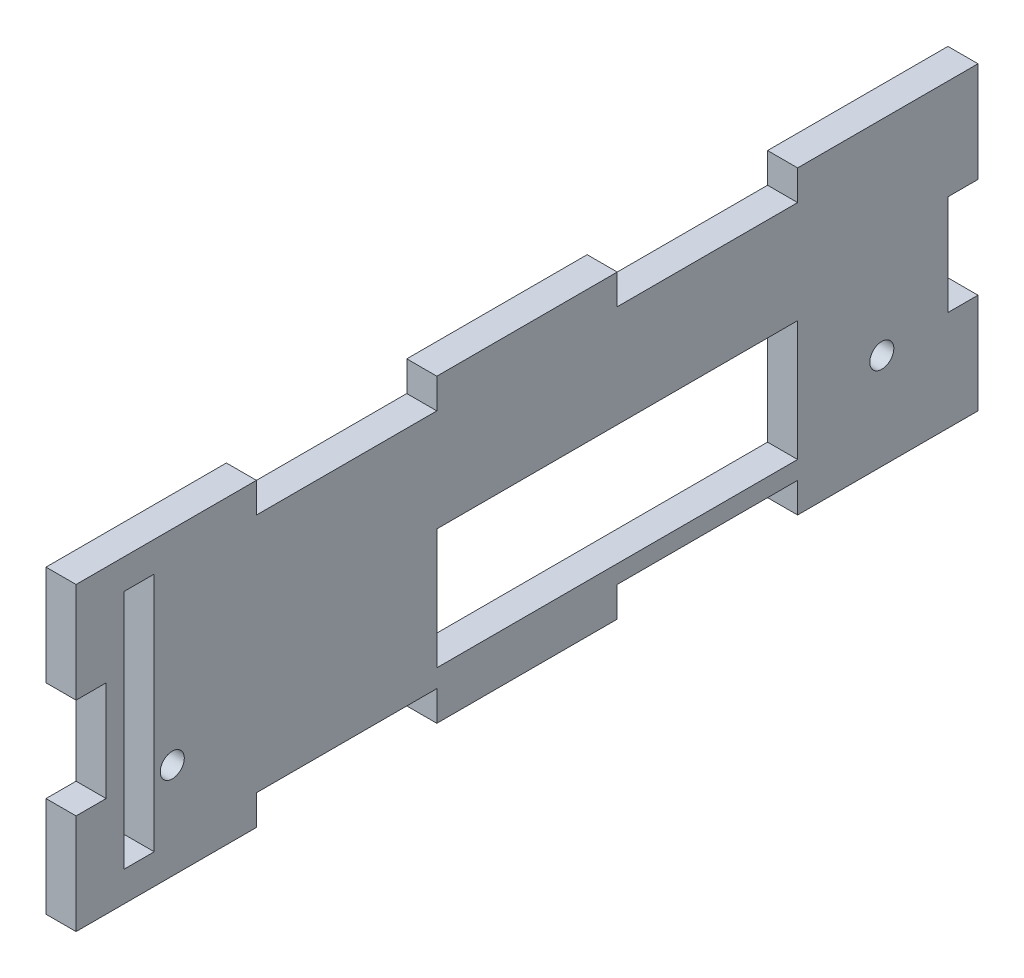
SolidWorks part; units mm, degrees
ref_plane "Alzado" through (0, 0, 0) normal (0, 0, 1) x (1, 0, 0)
ref_plane "Planta" through (0, 0, 0) normal (0, 1, 0) x (1, 0, 0)
ref_plane "Vista lateral" through (0, 0, 0) normal (1, 0, 0) x (0, 0, -1)
sketch "Croquis1" plane through (0, 0, 0) normal (1, 0, 0) x (0, 0, -1)
  line L0 (0, 33.3333) -> (5, 33.3333)
  line L1 (0, 0) -> (30, 0)
  line L2 (0, 0) -> (0, 16.6667)
  line L3 (0, 50) -> (30, 50)
  line L4 (150, 0) -> (150, 16.6667)
  line L5 (5, 33.3333) -> (5, 16.6667)
  line L6 (5, 16.6667) -> (0, 16.6667)
  line L7 (75, 40) -> (75, 31.2401) construction
  line L8 (145, 16.6667) -> (150, 16.6667)
  line L9 (145, 33.3333) -> (145, 16.6667)
  line L10 (150, 33.3333) -> (145, 33.3333)
  line L11 (30, 0) -> (30, 5)
  line L12 (30, 5) -> (60, 5)
  line L13 (60, 5) -> (60, 0)
  line L14 (120, 0) -> (120, 5)
  line L15 (90, 5) -> (90, 0)
  line L16 (120, 5) -> (90, 5)
  line L17 (5, 25) -> (8.4564, 25) construction
  line L18 (120, 50) -> (120, 45)
  line L19 (120, 45) -> (90, 45)
  line L20 (90, 45) -> (90, 50)
  line L21 (60, 45) -> (60, 50)
  line L22 (30, 50) -> (30, 45)
  line L23 (30, 45) -> (60, 45)
  line L24 (0, 33.3333) -> (0, 50)
  line L25 (60, 50) -> (90, 50)
  line L26 (60, 0) -> (90, 0)
  line L27 (120, 0) -> (150, 0)
  line L28 (120, 50) -> (150, 50)
  line L29 (150, 33.3333) -> (150, 50)
  circle A0 centre (16, 16) radius 2
  circle A1 centre (134, 16) radius 2
  dimension "D4" = 4
  dimension "D1" = 150
  dimension "D2" = 50
  dimension "D3" = 5
  dimension "D5" = 16.6667
  dimension "D6" = 30
  dimension "D7" = 30
  dimension "D8" = 5
  dimension "D9" = 16
  dimension "D10" = 16
extrude "Saliente-Extruir1" add sketch "Croquis1" along normal blind 5
sketch "Croquis2" plane through (5, 0, 0) normal (1, 0, 0) x (0, 0, -1)
  line L0 (90, 5) -> (120, 5) construction
  line L1 (120, 8) -> (60, 8)
  line L2 (120, 8) -> (120, 28)
  line L3 (120, 28) -> (60, 28)
  line L4 (60, 8) -> (60, 28)
  line L5 (145, 16.6667) -> (145, 33.3333) construction
  dimension "D1" = 60
  dimension "D2" = 20
  dimension "D3" = 3
  dimension "D4" = 25
extrude "Cortar-Extruir1" cut sketch "Croquis2" against normal blind 10
sketch "Croquis3" plane through (5, 0, 0) normal (1, 0, 0) x (0, 0, -1)
  line L0 (5, 33.3333) -> (5, 16.6667) construction
  line L1 (8, 45) -> (13, 45)
  line L2 (8, 45) -> (8, 5)
  line L3 (8, 5) -> (13, 5)
  line L4 (13, 45) -> (13, 5)
  line L5 (60, 45) -> (30, 45) construction
  line L6 (30, 5) -> (60, 5) construction
  dimension "D1" = 5
  dimension "D2" = 3
extrude "Cortar-Extruir2" cut sketch "Croquis3" against normal blind 10
